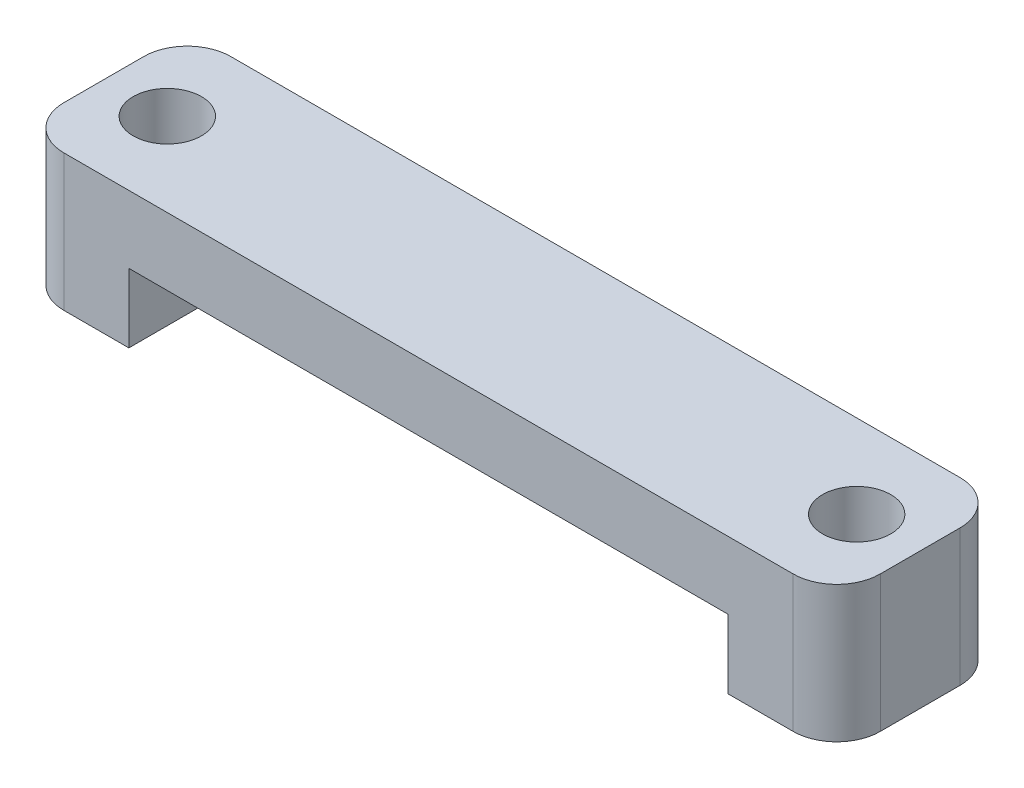
SolidWorks part; units mm, degrees
material "ASTM A36 Steel"
ref_plane "Front Plane" through (0, 0, 0) normal (0, 0, 1) x (1, 0, 0)
ref_plane "Top Plane" through (0, 0, 0) normal (0, 1, 0) x (1, 0, 0)
ref_plane "Right Plane" through (0, 0, 0) normal (1, 0, 0) x (0, 0, -1)
sketch "Sketch1" plane through (0, 0, 0) normal (0, 1, 0) x (1, 0, 0)
  line L1 (-14.2875, 2.921) -> (14.2875, 2.921)
  line L2 (-14.2875, 2.921) -> (-14.2875, -2.921)
  line L3 (-14.2875, -2.921) -> (14.2875, -2.921)
  line L4 (14.2875, 2.921) -> (14.2875, -2.921)
  circle A0 centre (12.065, 0) radius 1.1938
  circle A1 centre (-12.065, 0) radius 1.1938
  point P4 (14.2875, 0)
  point P5 (0, 2.921)
  dimension "D2" = 2.3876
  dimension "D1" = 5.842
  dimension "D3" = 28.575
  dimension "D4" = 12.065
  dimension "D5" = 12.065
extrude "Boss-Extrude1" add sketch "Sketch1" along normal blind 4.7752
fillet "Fillet1" radius 1.524 4 edges at (14.2875, 2.3876, -2.921) (-14.2875, 2.3876, -2.921) (-14.2875, 2.3876, 2.921) (14.2875, 2.3876, 2.921)
sketch "Sketch3" plane through (0, 0, 0) normal (0, 0, 1) x (1, 0, 0)
  line L1 (-10.4902, 2.413) -> (10.4902, 2.413)
  line L2 (-10.4902, 2.413) -> (-10.4902, 0)
  line L3 (-10.4902, 0) -> (10.4902, 0)
  line L4 (10.4902, 2.413) -> (10.4902, 0)
  dimension "D1" = 2.413
  dimension "D2" = 20.9804
extrude "Cut-Extrude2" cut sketch "Sketch3" against normal through all and the other way through all
sketch "Sketch4" plane through (0, 2.413, 0) normal (0, -1, 0) x (1, 0, 0)
  circle A0 centre (3.9624, 0) radius 1.1684
  circle A1 centre (-3.9624, 0) radius 1.1684
  dimension "D3" = 2.3368
  dimension "D1" = 3.9624
  dimension "D2" = 3.9624
extrude "Boss-Extrude3" [suppressed] add sketch "Sketch4" along normal blind 0.254
